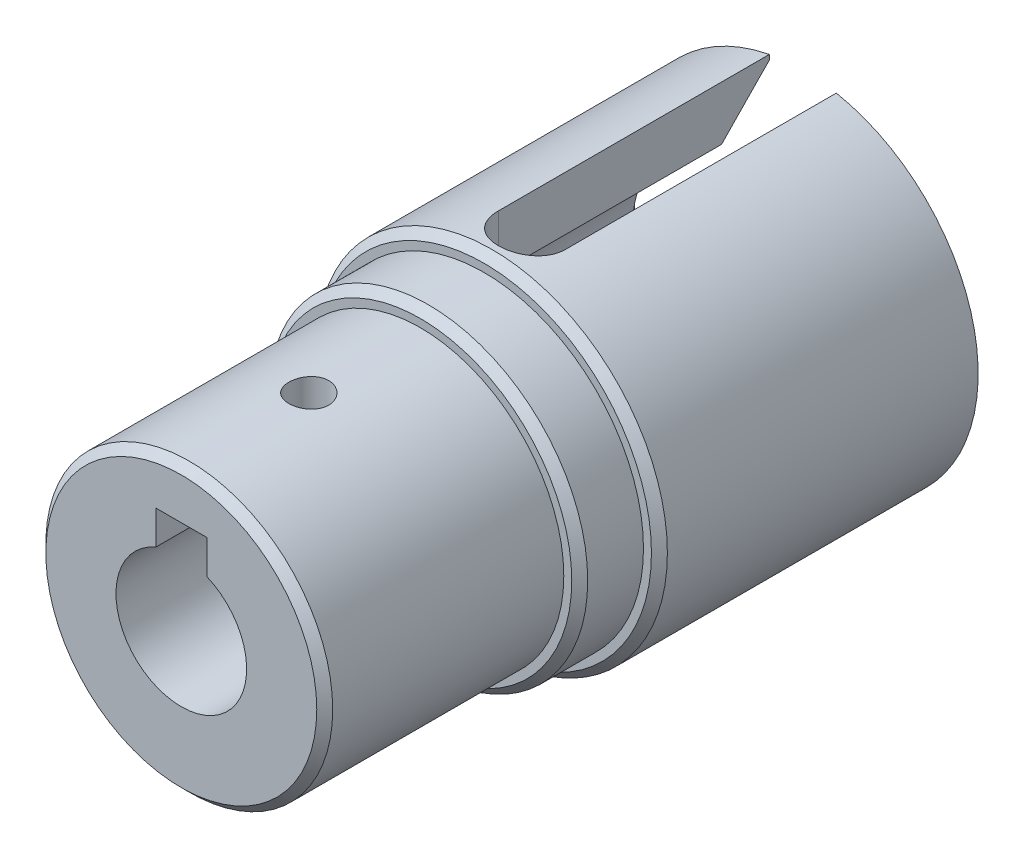
SolidWorks part; units mm, degrees
material "7075-O (SS)"
ref_plane "前视基准面" through (0, 0, 0) normal (0, 0, 1) x (1, 0, 0)
ref_plane "上视基准面" through (0, 0, 0) normal (0, 1, 0) x (1, 0, 0)
ref_plane "右视基准面" through (0, 0, 0) normal (1, 0, 0) x (0, 0, -1)
sketch "草图1" plane through (0, 0, 0) normal (0, 0, 1) x (1, 0, 0)
  circle A0 centre (0, 0) radius 11
  dimension "D1" = 22
extrude "凸台-拉伸1" add sketch "草图1" along normal blind 29
sketch "草图2" plane through (0, 0, 29) normal (0, 0, 1) x (1, 0, 0)
  circle A0 centre (0, 0) radius 10
  dimension "D1" = 20
extrude "切除-拉伸1" cut sketch "草图2" against normal blind 9 flip side to cut
sketch "草图3" plane through (0, 0, 0) normal (0, 0, -1) x (-1, 0, 0)
  circle A0 centre (0, 0) radius 7.7
  dimension "D1" = 15.4
extrude "切除-拉伸2" cut sketch "草图3" against normal blind 20
sketch "草图4" plane through (0, 0, 0) normal (0, 1, 0) x (1, 0, 0)
  line L0 (-2.1, -17) -> (-2.1, 0)
  line L1 (11, 0) -> (-11, 0) construction
  line L2 (2.1, -17) -> (2.1, 0)
  line L3 (7.7, 0) -> (-7.7, 0) construction
  line L4 (2.1, 0) -> (-2.1, 0)
  circle A0 centre (0, -17) radius 2.1
  dimension "D2" = 4.2
  dimension "D1" = 17
extrude "切除-拉伸3" cut sketch "草图4" against normal mid plane 50 contours A0 L2 L4 L0 | A0
chamfer "倒角1" distance 3 angle 45 2 edges at (7.7, 0, 0) (-7.7, 0, 0)
sketch "草图5" plane through (0, 0, 29) normal (0, 0, 1) x (1, 0, 0)
  circle A1 centre (0, 0) radius 10
  circle A2 centre (0, 0) radius 10
  dimension "D1" = 0
extrude "凸台-拉伸2" add sketch "草图5" along normal blind 10
sketch "草图6" plane through (0, 0, 39) normal (0, 0, 1) x (1, 0, 0)
  circle A0 centre (0, 0) radius 4
  dimension "D1" = 8
extrude "切除-拉伸5" cut sketch "草图6" against normal up to surface (19 mm away) up to face at (-7.7, 0, 20)
sketch "草图8" plane through (0, 0, 39) normal (0, 0, 1) x (1, 0, 0)
  circle A0 centre (0, 0) radius 9
  dimension "D1" = 18
extrude "切除-拉伸7" cut sketch "草图8" against normal blind 15 flip side to cut
sketch "草图9" plane through (0, 0, 0) normal (0, 1, 0) x (1, 0, 0)
  line L0 (-9, -39) -> (9, -39) construction
  circle A0 centre (0, -31) radius 1.25
  dimension "D1" = 8
  dimension "D2" = 2.5
extrude "切除-拉伸8" cut sketch "草图9" against normal mid plane 50
chamfer "倒角3" distance 0.5 angle 45 3 edges at (10, 0, 24) (11, 0, 20) (9, 0, 39)
sketch "草图10" plane through (0, 0, 39) normal (0, 0, 1) x (1, 0, 0)
  line L0 (0, 0) -> (0, 5.8) construction
  line L1 (-1.5, 5.8) -> (1.5, 5.8)
  line L2 (1.5, 5.8) -> (1.5, 3.7081)
  line L3 (-1.5, 5.8) -> (-1.5, 3.7081)
  circle A0 centre (0, 0) radius 4
  point P6 (0, 5.8)
  circle M4 centre (0, 0) radius 4
  dimension "D3" = 8
  dimension "D1" = 5.8
  dimension "D2" = 3
extrude "切除-拉伸9" cut sketch "草图10" against normal up to surface (19 mm away) contours L0 A0 L2 L1 | L0 L1 L3 M4 up to face at (-4, 0, 20)
sketch "草图11" plane through (0, 0, 39) normal (0, 0, 1) x (1, 0, 0)
  line L9 (1.6, 3.7749) -> (1.6, 5.9)
  line L10 (1.6, 5.9) -> (-1.6, 5.9)
  line L11 (-1.6, 5.9) -> (-1.6, 3.7749)
  line L12 (1.6, 3.7749) -> (1.6, 5.9)
  line L13 (1.6, 5.9) -> (-1.6, 5.9)
  line L14 (-1.6, 5.9) -> (-1.6, 3.7749)
  arc A5 (-1.6, 3.7749) -> (1.6, 3.7749) centre (0, 0) ccw
  arc A6 (-1.6, 3.7749) -> (1.6, 3.7749) centre (0, 0) ccw
  dimension "D1" = 0.1
extrude "切除-拉伸10" cut sketch "草图11" against normal up to surface (19 mm away) up to face at (0, 2.827, 20)
